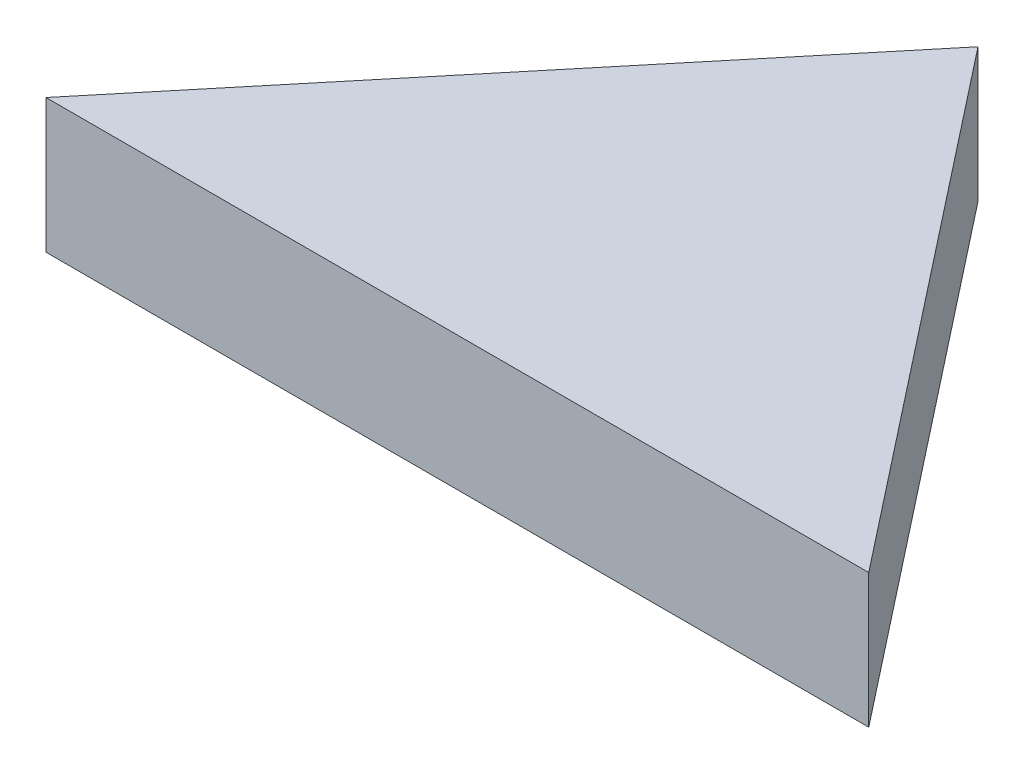
SolidWorks part; units mm, degrees
ref_plane "Front Plane" through (0, 0, 0) normal (0, 0, 1) x (1, 0, 0)
ref_plane "Top Plane" through (0, 0, 0) normal (0, 1, 0) x (1, 0, 0)
ref_plane "Right Plane" through (0, 0, 0) normal (1, 0, 0) x (0, 0, -1)
sketch "Sketch1" plane through (0, 0, 0) normal (0, 1, 0) x (1, 0, 0)
  line L3 (0, 0) -> (3.1496, 3.8057)
  line L4 (3.1496, 3.8057) -> (6.14, 0)
  line L5 (6.14, 0) -> (0, 0)
  point P3 (0, 0)
  point P7 (0.1703, 0)
  dimension "D1" = 4.94
  dimension "D2" = 4.84
  dimension "D3" = 6.14
extrude "Boss-Extrude1" add sketch "Sketch1" along normal blind 1
sketch "Sketch2" plane through (0, 1, 0) normal (0, 1, 0) x (1, 0, 0)
  line L0 (1.0277, 0.4748) -> (1.4277, 0.4748)
  line L6 (0.5655, 0.4748) -> (0.9655, 0.4748)
  line L7 (0.5655, 0.4748) -> (0.5655, 0.0748)
  line L8 (0.5655, 0.0748) -> (0.9655, 0.0748)
  line L9 (0.9655, 0.4748) -> (0.9655, 0.0748)
  line L10 (1.0277, 0.4748) -> (1.0277, 0.0748)
  line L11 (1.0277, 0.0748) -> (1.4277, 0.0748)
  line L12 (1.4277, 0.4748) -> (1.4277, 0.0748)
  line L13 (1.4985, 0.4748) -> (1.8985, 0.4748)
  line L14 (1.4985, 0.4748) -> (1.4985, 0.0748)
  line L15 (1.4985, 0.0748) -> (1.8985, 0.0748)
  line L16 (1.8985, 0.4748) -> (1.8985, 0.0748)
  line L17 (1.9734, 0.4748) -> (2.3734, 0.4748)
  line L18 (1.9734, 0.4748) -> (1.9734, 0.0748)
  line L19 (1.9734, 0.0748) -> (2.3734, 0.0748)
  line L20 (2.3734, 0.4748) -> (2.3734, 0.0748)
  line L33 (3.8086, 0.4786) -> (4.2086, 0.4786)
  line L34 (3.8086, 0.4786) -> (3.8086, 0.0786)
  line L35 (3.8086, 0.0786) -> (4.2086, 0.0786)
  line L36 (4.2086, 0.4786) -> (4.2086, 0.0786)
  line L37 (4.2836, 0.4786) -> (4.6836, 0.4786)
  line L38 (4.2836, 0.4786) -> (4.2836, 0.0786)
  line L39 (4.2836, 0.0786) -> (4.6836, 0.0786)
  line L40 (4.6836, 0.4786) -> (4.6836, 0.0786)
  line L41 (4.7705, 0.4786) -> (5.1705, 0.4786)
  line L42 (4.7705, 0.4786) -> (4.7705, 0.0786)
  line L43 (4.7705, 0.0786) -> (5.1705, 0.0786)
  line L44 (5.1705, 0.4786) -> (5.1705, 0.0786)
  line L45 (5.2495, 0.4786) -> (5.6495, 0.4786)
  line L46 (5.2495, 0.4786) -> (5.2495, 0.0786)
  line L47 (5.2495, 0.0786) -> (5.6495, 0.0786)
  line L48 (5.6495, 0.4786) -> (5.6495, 0.0786)
  line L53 (1.0823, 0.9557) -> (1.4823, 0.9557)
  line L54 (1.0823, 0.9557) -> (1.0823, 0.5557)
  line L55 (1.0823, 0.5557) -> (1.4823, 0.5557)
  line L56 (1.4823, 0.9557) -> (1.4823, 0.5557)
  line L57 (1.5369, 0.9557) -> (1.9369, 0.9557)
  line L58 (1.5369, 0.9557) -> (1.5369, 0.5557)
  line L59 (1.5369, 0.5557) -> (1.9369, 0.5557)
  line L60 (1.9369, 0.9557) -> (1.9369, 0.5557)
  line L61 (1.9948, 0.9557) -> (2.3948, 0.9557)
  line L62 (1.9948, 0.9557) -> (1.9948, 0.5557)
  line L63 (1.9948, 0.5557) -> (2.3948, 0.5557)
  line L64 (2.3948, 0.9557) -> (2.3948, 0.5557)
  line L65 (2.4377, 0.9557) -> (2.8377, 0.9557)
  line L66 (2.4377, 0.9557) -> (2.4377, 0.5557)
  line L67 (2.4377, 0.5557) -> (2.8377, 0.5557)
  line L68 (2.8377, 0.9557) -> (2.8377, 0.5557)
  line L69 (3.2707, 0.9745) -> (3.6707, 0.9745)
  line L70 (3.2707, 0.9745) -> (3.2707, 0.5745)
  line L71 (3.2707, 0.5745) -> (3.6707, 0.5745)
  line L72 (3.6707, 0.9745) -> (3.6707, 0.5745)
  line L73 (3.7225, 0.9745) -> (4.1225, 0.9745)
  line L74 (3.7225, 0.9745) -> (3.7225, 0.5745)
  line L75 (3.7225, 0.5745) -> (4.1225, 0.5745)
  line L76 (4.1225, 0.9745) -> (4.1225, 0.5745)
  line L77 (4.1573, 0.9745) -> (4.5573, 0.9745)
  line L78 (4.1573, 0.9745) -> (4.1573, 0.5745)
  line L79 (4.1573, 0.5745) -> (4.5573, 0.5745)
  line L80 (4.5573, 0.9745) -> (4.5573, 0.5745)
  line L81 (4.6053, 0.9745) -> (5.0053, 0.9745)
  line L82 (4.6053, 0.9745) -> (4.6053, 0.5745)
  line L83 (4.6053, 0.5745) -> (5.0053, 0.5745)
  line L84 (5.0053, 0.9745) -> (5.0053, 0.5745)
  line L89 (1.2467, 1.4443) -> (1.6467, 1.4443)
  line L90 (1.2467, 1.4443) -> (1.2467, 1.0443)
  line L91 (1.2467, 1.0443) -> (1.6467, 1.0443)
  line L92 (1.6467, 1.4443) -> (1.6467, 1.0443)
  line L93 (1.7031, 1.4443) -> (2.1031, 1.4443)
  line L94 (1.7031, 1.4443) -> (1.7031, 1.0627)
  line L95 (1.7031, 1.0627) -> (2.1031, 1.0627)
  line L96 (2.1031, 1.4443) -> (2.1031, 1.0627)
  line L97 (2.1349, 1.4443) -> (2.5349, 1.4443)
  line L98 (2.1349, 1.4443) -> (2.1349, 1.0596)
  line L99 (2.1349, 1.0596) -> (2.5349, 1.0596)
  line L100 (2.5349, 1.4443) -> (2.5349, 1.0596)
  line L101 (2.5608, 1.4443) -> (2.9608, 1.4443)
  line L102 (2.5608, 1.4443) -> (2.5608, 1.0627)
  line L103 (2.5608, 1.0627) -> (2.9608, 1.0627)
  line L104 (2.9608, 1.4443) -> (2.9608, 1.0627)
  line L105 (3.2249, 1.4403) -> (3.6249, 1.4403)
  line L106 (3.2249, 1.4403) -> (3.2249, 1.0403)
  line L107 (3.2249, 1.0403) -> (3.6249, 1.0403)
  line L108 (3.6249, 1.4403) -> (3.6249, 1.0403)
  line L109 (3.6744, 1.4403) -> (4.0744, 1.4403)
  line L110 (3.6744, 1.4403) -> (3.6744, 1.0403)
  line L111 (3.6744, 1.0403) -> (4.0744, 1.0403)
  line L112 (4.0744, 1.4403) -> (4.0744, 1.0403)
  line L113 (4.1454, 1.4403) -> (4.5454, 1.4403)
  line L114 (4.1454, 1.4403) -> (4.1454, 1.0403)
  line L115 (4.1454, 1.0403) -> (4.5454, 1.0403)
  line L116 (4.5454, 1.4403) -> (4.5454, 1.0403)
  line L117 (4.6121, 1.4403) -> (5.0121, 1.4403)
  line L118 (4.6121, 1.4403) -> (4.6121, 1.0403)
  line L119 (4.6121, 1.0403) -> (5.0121, 1.0403)
  line L120 (5.0121, 1.4403) -> (5.0121, 1.0403)
  line L125 (2.237, 1.9635) -> (2.637, 1.9635)
  line L126 (2.237, 1.9635) -> (2.237, 1.5528)
  line L127 (2.237, 1.5528) -> (2.637, 1.5528)
  line L128 (2.637, 1.9635) -> (2.637, 1.5528)
  line L129 (2.6864, 1.9635) -> (3.0772, 1.9635)
  line L130 (2.6864, 1.9635) -> (2.6864, 1.5605)
  line L131 (2.6864, 1.5605) -> (3.0772, 1.5605)
  line L132 (3.0772, 1.9635) -> (3.0772, 1.5605)
  line L133 (3.1948, 1.9635) -> (3.5948, 1.9635)
  line L134 (3.1948, 1.9635) -> (3.1948, 1.5498)
  line L135 (3.1948, 1.5498) -> (3.5948, 1.5498)
  line L136 (3.5948, 1.9635) -> (3.5948, 1.5498)
  line L137 (3.6488, 1.9635) -> (4.0488, 1.9635)
  line L138 (3.6488, 1.9635) -> (3.6488, 1.5498)
  line L139 (3.6488, 1.5498) -> (4.0488, 1.5498)
  line L140 (4.0488, 1.9635) -> (4.0488, 1.5498)
  line L145 (2.2374, 2.5046) -> (2.6374, 2.5046)
  line L146 (2.2374, 2.5046) -> (2.2374, 2.1046)
  line L147 (2.2374, 2.1046) -> (2.6374, 2.1046)
  line L148 (2.6374, 2.5046) -> (2.6374, 2.1046)
  line L149 (2.7101, 2.5046) -> (3.1101, 2.5046)
  line L150 (2.7101, 2.5046) -> (2.7101, 2.1046)
  line L151 (2.7101, 2.1046) -> (3.1101, 2.1046)
  line L152 (3.1101, 2.5046) -> (3.1101, 2.1046)
  line L153 (3.1692, 2.5046) -> (3.5692, 2.5046)
  line L154 (3.1692, 2.5046) -> (3.1692, 2.1046)
  line L155 (3.1692, 2.1046) -> (3.5692, 2.1046)
  line L156 (3.5692, 2.5046) -> (3.5692, 2.1046)
  line L157 (3.6246, 2.5046) -> (4.0246, 2.5046)
  line L158 (3.6246, 2.5046) -> (3.6246, 2.1046)
  line L159 (3.6246, 2.1046) -> (4.0246, 2.1046)
  line L160 (4.0246, 2.5046) -> (4.0246, 2.1046)
  line L161 (2.5069, 3.0191) -> (2.9069, 3.0191)
  line L162 (2.5069, 3.0191) -> (2.5069, 2.6191)
  line L163 (2.5069, 2.6191) -> (2.9069, 2.6191)
  line L164 (2.9069, 3.0191) -> (2.9069, 2.6191)
  line L165 (2.9313, 3.0191) -> (3.3313, 3.0191)
  line L166 (2.9313, 3.0191) -> (2.9313, 2.6191)
  line L167 (2.9313, 2.6191) -> (3.3313, 2.6191)
  line L168 (3.3313, 3.0191) -> (3.3313, 2.6191)
  line L169 (3.3597, 3.0191) -> (3.7597, 3.0191)
  line L170 (3.3597, 3.0191) -> (3.3597, 2.6191)
  line L171 (3.3597, 2.6191) -> (3.7597, 2.6191)
  line L172 (3.7597, 3.0191) -> (3.7597, 2.6191)
  line L173 (2.9263, 3.4623) -> (3.3263, 3.4623)
  line L174 (2.9263, 3.4623) -> (2.9263, 3.0623)
  line L175 (2.9263, 3.0623) -> (3.3263, 3.0623)
  line L176 (3.3263, 3.4623) -> (3.3263, 3.0623)
  line L177 (2.125, 2.5676) -> (4.1225, 2.5676) construction
  line L178 (1.2467, 1.5064) -> (4.9564, 1.5064) construction
  line L179 (1.676, 2.0251) -> (4.5488, 2.0251) construction
  line L180 (5.3504, 1.0049) -> (0.8317, 1.0049) construction
  line L181 (3.127, 1.5064) -> (3.127, 0) construction
  line L182 (0.4599, 0.5557) -> (5.7033, 0.5557) construction
  line L183 (6.14, 0) -> (3.1496, 3.8057) construction
  line L184 (3.1496, 3.8057) -> (0, 0) construction
  line L185 (0, 0) -> (6.14, 0) construction
  line L186 (0.6608, 2.4357) -> (1.0608, 2.4357)
  line L187 (0.6608, 2.4357) -> (0.6608, 2.0357)
  line L188 (0.6608, 2.0357) -> (1.0608, 2.0357)
  line L189 (1.0608, 2.4357) -> (1.0608, 2.0357)
  point P44 (0.9555, 2.2357)
  point P45 (0.7571, 2.2357)
  point P46 (0.8499, 2.2357)
  point P47 (0.8499, 2.3339)
  point P82 (0.9555, 2.3339)
  point P117 (0.7571, 2.3339)
  point P118 (0.8499, 2.1304)
  point P119 (0.7571, 2.1304)
  point P120 (0.9555, 2.1304)
  dimension "D1" = 0.4
  dimension "D2" = 0.4
